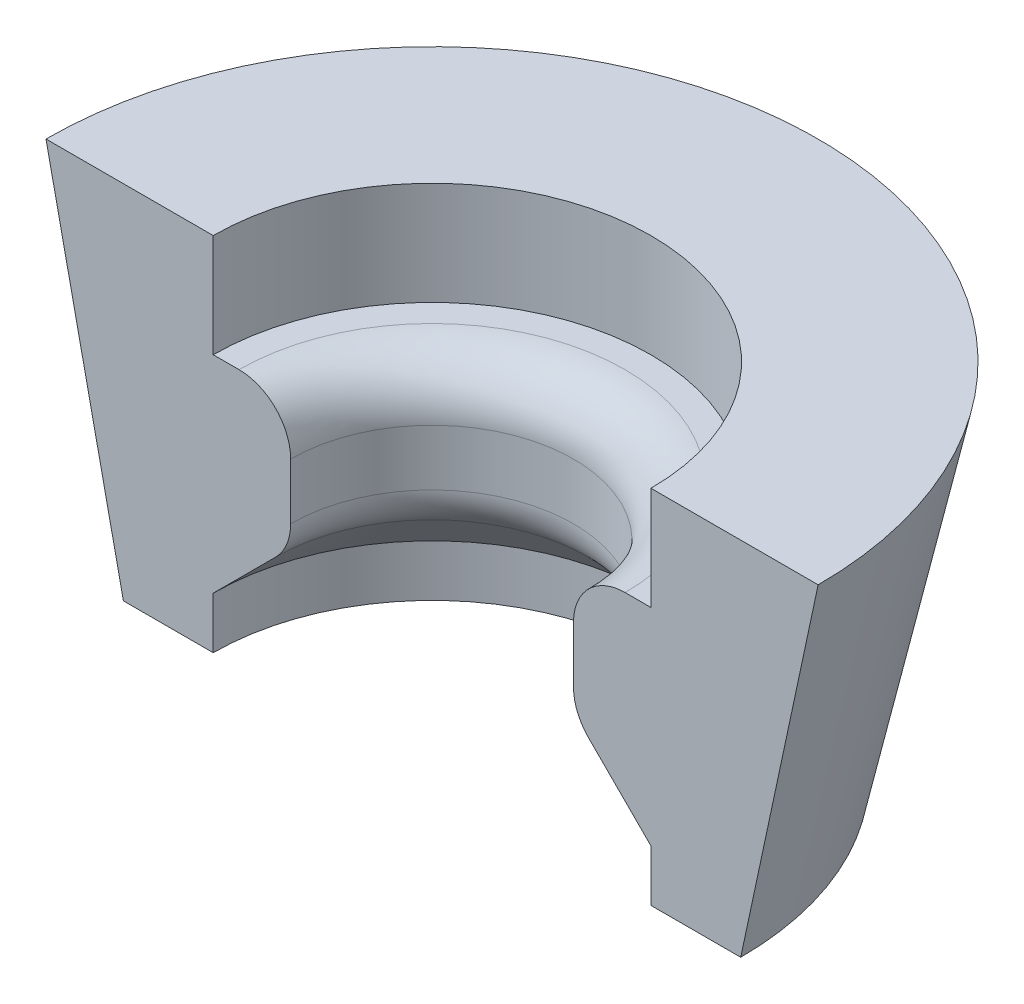
SolidWorks part; units mm, degrees
ref_plane "Front Plane" through (0, 0, 0) normal (0, 0, 1) x (1, 0, 0)
ref_plane "Top Plane" through (0, 0, 0) normal (0, 1, 0) x (1, 0, 0)
ref_plane "Right Plane" through (0, 0, 0) normal (1, 0, 0) x (0, 0, -1)
sketch "Sketch1" plane through (0, 0, 0) normal (0, 0, 1) x (1, 0, 0)
  line L0 (-3.3655, 1.5875) -> (-3.3655, 3.175)
  line L1 (-3.3655, 1.5875) -> (3.3655, 1.5875) construction
  line L2 (-3.3655, 1.5875) -> (-3.3655, -1.5875) construction
  line L3 (-3.3655, -1.5875) -> (3.3655, -1.5875) construction
  line L4 (3.3655, 1.5875) -> (3.3655, -1.5875) construction
  line L5 (-3.3655, 1.5875) -> (3.3655, -1.5875) construction
  line L6 (-3.3655, -1.5875) -> (3.3655, 1.5875) construction
  line L7 (-3.3655, 3.175) -> (-5.9372, 3.175)
  line L8 (-5.9372, 3.175) -> (-4.7466, -2.3812)
  line L9 (-4.7466, -2.3812) -> (-3.3655, -2.3812)
  line L10 (-3.3655, -2.3812) -> (-3.3655, -1.5875)
  line L11 (-3.3655, 1.5875) -> (-2.9686, 1.5875)
  line L12 (-2.1749, 0.7938) -> (-2.1749, -0.0681)
  line L13 (-2.4074, -0.6294) -> (-3.3655, -1.5875)
  line L14 (0, 1.5875) -> (0, -1.5875) construction
  arc A0 (-2.9686, 1.5875) -> (-2.1749, 0.7938) centre (-2.9686, 0.7938) cw
  arc A1 (-2.1749, -0.0681) -> (-2.4074, -0.6294) centre (-2.9686, -0.0681) cw
  point P0 (0, 0)
  point P14 (-2.1749, 1.5875)
  dimension "D9" = 0.7937
  dimension "D1" = 6.731
  dimension "D2" = 3.175
  dimension "D3" = 5.9372
  dimension "D4" = 4.7466
  dimension "D5" = 0.7937
  dimension "D6" = 1.5875
  dimension "D7" = 45
  dimension "D8" = 1.1906
revolve "Revolve1" add sketch "Sketch1" angle 180 about L14
